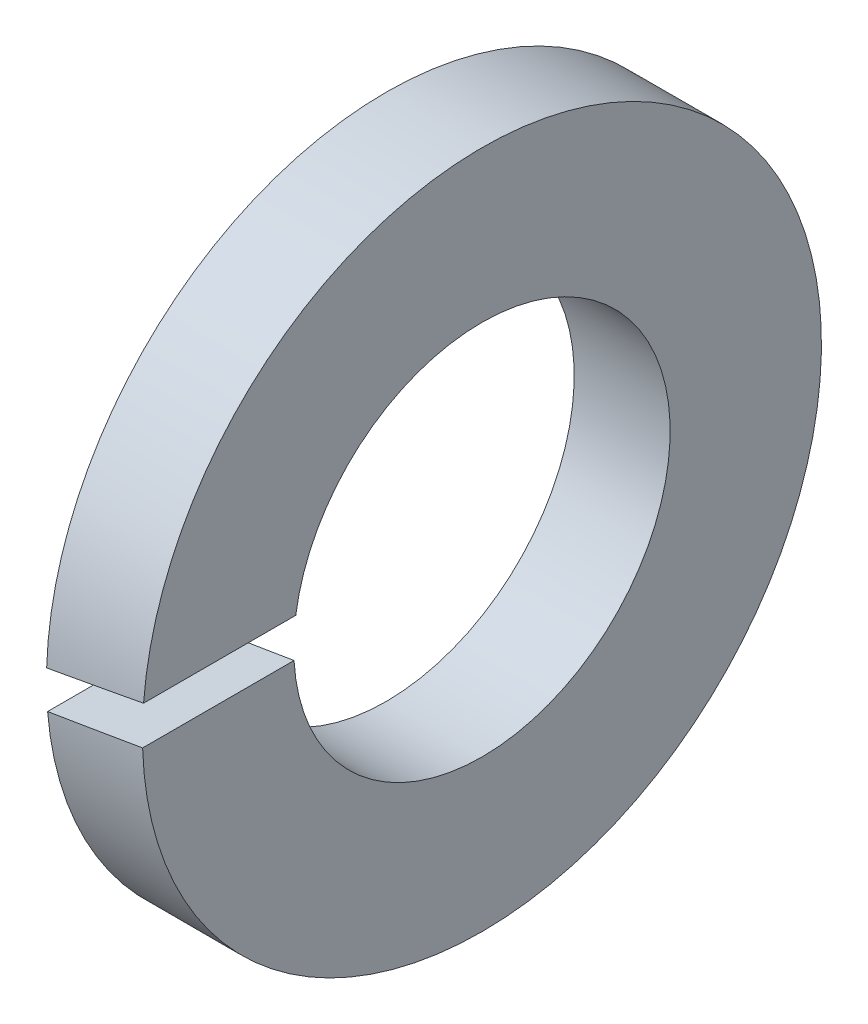
SolidWorks part; units mm, degrees
ref_plane "Front Plane" through (0, 0, 0) normal (0, 0, 1) x (1, 0, 0)
ref_plane "Top Plane" through (0, 0, 0) normal (0, 1, 0) x (1, 0, 0)
ref_plane "Right Plane" through (0, 0, 0) normal (1, 0, 0) x (0, 0, -1)
sketch "Sketch1" plane through (0, 0, 0) normal (0, 0, 1) x (1, 0, 0)
  line L0 (-1.3, 0) -> (0, 0) construction
  line L2 (-1.3, 2.55) -> (0, 2.55)
  line L3 (-1.3, 2.55) -> (-1.3, 4.6)
  line L4 (-1.3, 4.6) -> (0, 4.6)
  line L5 (0, 2.55) -> (0, 4.6)
  dimension "MSM_47" = 1.3
  dimension "MSM_48" = 9.2
  dimension "MSM_49" = 5.1
revolve "Revolve1" add sketch "Sketch1" angle 360 about L0
sketch "Sketch2" plane through (0, 0, 0) normal (0, 0, 1) x (1, 0, 0)
  line L0 (-1.3, 0.1443) -> (0, 0.3735)
  line L1 (0, -0.1443) -> (-1.3, -0.3735)
  line L2 (0, -0.1443) -> (0, 0.3735)
  line L3 (-1.3, 0.1443) -> (-1.3, -0.3735)
  line L4 (-1.3, 0.1443) -> (0, -0.1443) construction
  point P4 (-0.65, 0)
  dimension "MSM_47" = 1.3
  dimension "FIX_2" = 0.51
  dimension "FIX_3" = 80
extrude "Cut-Extrude1" cut sketch "Sketch2" along normal through all
equation "\"FIX_2@Sketch2\"= \"MSM_49@Sketch1\" * 0.1"
